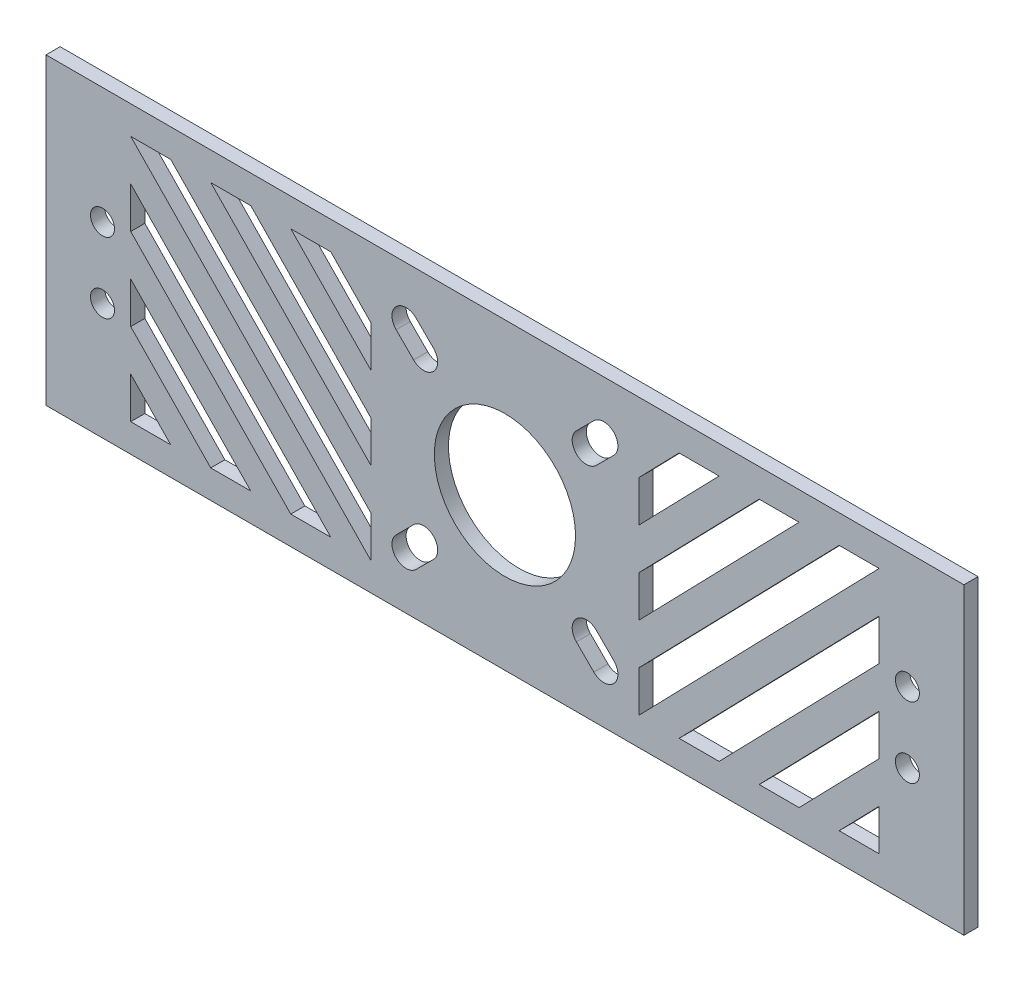
SolidWorks part; units mm, degrees
material "黑板"
ref_plane "前视基准面" through (0, 0, 0) normal (0, 0, 1) x (1, 0, 0)
ref_plane "上视基准面" through (0, 0, 0) normal (0, 1, 0) x (1, 0, 0)
ref_plane "右视基准面" through (0, 0, 0) normal (1, 0, 0) x (0, 0, -1)
sketch "草图1" plane through (0, 0, 0) normal (0, 0, 1) x (1, 0, 0)
  line L1 (-65, 21.5) -> (65, 21.5)
  line L2 (-65, 21.5) -> (-65, -21.5)
  line L3 (-65, -21.5) -> (65, -21.5)
  line L4 (65, 21.5) -> (65, -21.5)
  line L5 (-65, 21.5) -> (65, -21.5) construction
  line L6 (-65, -21.5) -> (65, 21.5) construction
  point P0 (0, 0)
  dimension "D1" = 130
  dimension "D2" = 43
extrude "凸台-拉伸1" add sketch "草图1" along normal blind 2
sketch "草图2" plane through (0, 0, 2) normal (0, 0, 1) x (1, 0, 0)
  line L0 (-14, 14) -> (-11.5251, 11.5251) construction
  line L1 (-16, 16) -> (16, 16) construction
  line L2 (-16, 16) -> (-16, -16) construction
  line L3 (-16, -16) -> (16, -16) construction
  line L4 (16, 16) -> (16, -16) construction
  line L5 (-16, 16) -> (16, -16) construction
  line L6 (-16, -16) -> (16, 16) construction
  line L7 (-12.5858, 15.4142) -> (-10.1109, 12.9393)
  line L8 (-15.4142, 12.5858) -> (-12.9393, 10.1109)
  line L9 (14, 14) -> (11.5251, 11.5251) construction
  line L10 (15.4142, 12.5858) -> (12.9393, 10.1109)
  line L11 (12.5858, 15.4142) -> (10.1109, 12.9393)
  line L12 (14, -14) -> (11.5251, -11.5251) construction
  line L13 (12.5858, -15.4142) -> (10.1109, -12.9393)
  line L14 (15.4142, -12.5858) -> (12.9393, -10.1109)
  line L15 (-14, -14) -> (-11.5251, -11.5251) construction
  line L16 (-15.4142, -12.5858) -> (-12.9393, -10.1109)
  line L17 (-12.5858, -15.4142) -> (-10.1109, -12.9393)
  arc A0 (-12.5858, 15.4142) -> (-15.4142, 12.5858) centre (-14, 14) ccw
  arc A1 (-12.9393, 10.1109) -> (-10.1109, 12.9393) centre (-11.5251, 11.5251) ccw
  arc A2 (15.4142, 12.5858) -> (12.5858, 15.4142) centre (14, 14) ccw
  arc A3 (10.1109, 12.9393) -> (12.9393, 10.1109) centre (11.5251, 11.5251) ccw
  arc A4 (12.5858, -15.4142) -> (15.4142, -12.5858) centre (14, -14) ccw
  arc A5 (12.9393, -10.1109) -> (10.1109, -12.9393) centre (11.5251, -11.5251) ccw
  arc A6 (-15.4142, -12.5858) -> (-12.5858, -15.4142) centre (-14, -14) ccw
  arc A7 (-10.1109, -12.9393) -> (-12.9393, -10.1109) centre (-11.5251, -11.5251) ccw
  point P0 (0, 0)
  point P8 (-12.7626, 12.7626)
  point P13 (0, 0)
  point P14 (11.5251, 11.5251)
  point P18 (12.7626, 12.7626)
  point P25 (12.7626, -12.7626)
  point P32 (-12.7626, -12.7626)
  point P37 (0, 0)
  dimension "D3" = 2
  dimension "D1" = 32
  dimension "D2" = 3.5
  dimension "D4" = 4
extrude "切除-拉伸1" cut sketch "草图2" against normal through all
sketch "草图3" plane through (0, 0, 2) normal (0, 0, 1) x (1, 0, 0)
  line L0 (57, -5) -> (57, 5) construction
  line L1 (57, 0) -> (65, 0) construction
  line L2 (65, -21.5) -> (65, 21.5) construction
  line L3 (0, 0) -> (0, 32.0098) construction
  circle A0 centre (57, 5) radius 1.7
  circle A1 centre (57, -5) radius 1.7
  circle A2 centre (-57, -5) radius 1.7
  circle A3 centre (-57, 5) radius 1.7
  dimension "D1" = 10
  dimension "D2" = 8
  dimension "3.4" = 3.4
extrude "切除-拉伸2" cut sketch "草图3" against normal through all
sketch "草图4" plane through (0, 0, 2) normal (0, 0, 1) x (1, 0, 0)
  line L0 (-53, 17.5) -> (-53, -17.5)
  line L1 (-53, -17.5) -> (-19, -17.5)
  line L2 (-19, -17.5) -> (-19, 17.5)
  line L3 (-19, 17.5) -> (-53, 17.5)
  line L4 (-57, 5) -> (-57, -5) construction
  line L5 (65, 21.5) -> (-65, 21.5) construction
  line L6 (-65, -21.5) -> (65, -21.5) construction
  line L7 (0, 0) -> (0, 37.7139) construction
  line L8 (19, -17.5) -> (19, 17.5)
  line L9 (53, -17.5) -> (19, -17.5)
  line L10 (53, 17.5) -> (53, -17.5)
  line L11 (19, 17.5) -> (53, 17.5)
  arc A0 (-12.5858, 15.4142) -> (-15.4142, 12.5858) centre (-14, 14) ccw construction
  circle A1 centre (0, 0) radius 10
  dimension "D5" = 20
  dimension "D1" = 4
  dimension "D2" = 4
  dimension "D3" = 4
  dimension "D4" = 5
extrude "切除-拉伸3" cut sketch "草图4" against normal through all
sketch "草图6" plane through (0, 0, 2) normal (0, 0, 1) x (1, 0, 0)
  line L0 (-53, 17.5) -> (-19, -17.5)
  line L1 (-47.3333, 17.5) -> (-13.3333, -17.5)
  line L2 (-41.6667, 17.5) -> (-7.6667, -17.5)
  line L3 (-36, 17.5) -> (-2, -17.5)
  line L4 (-30.3333, 17.5) -> (3.6667, -17.5)
  line L5 (-58.6667, 17.5) -> (-24.6667, -17.5)
  line L6 (-53, 17.5) -> (-19, -17.5)
  line L7 (-47.3333, 17.5) -> (-13.3333, -17.5)
  line L8 (-41.6667, 17.5) -> (-7.6667, -17.5)
  line L9 (-36, 17.5) -> (-2, -17.5)
  line L10 (-64.3333, 17.5) -> (-30.3333, -17.5)
  line L11 (-58.6667, 17.5) -> (-24.6667, -17.5)
  line L12 (-53, 17.5) -> (-19, -17.5)
  line L13 (-47.3333, 17.5) -> (-13.3333, -17.5)
  line L14 (-41.6667, 17.5) -> (-7.6667, -17.5)
  line L15 (-70, 17.5) -> (-36, -17.5)
  line L16 (-64.3333, 17.5) -> (-30.3333, -17.5)
  line L17 (-58.6667, 17.5) -> (-24.6667, -17.5)
  line L18 (-53, 17.5) -> (-19, -17.5)
  line L19 (-47.3333, 17.5) -> (-13.3333, -17.5)
  line L20 (-75.6667, 17.5) -> (-41.6667, -17.5)
  line L21 (-70, 17.5) -> (-36, -17.5)
  line L22 (-64.3333, 17.5) -> (-30.3333, -17.5)
  line L23 (-58.6667, 17.5) -> (-24.6667, -17.5)
  line L24 (-53, 17.5) -> (-19, -17.5)
  line L25 (-81.3333, 17.5) -> (-47.3333, -17.5)
  line L26 (-75.6667, 17.5) -> (-41.6667, -17.5)
  line L27 (-70, 17.5) -> (-36, -17.5)
  line L28 (-64.3333, 17.5) -> (-30.3333, -17.5)
  line L29 (-58.6667, 17.5) -> (-24.6667, -17.5)
  line L30 (-87, 17.5) -> (-53, -17.5)
  line L31 (-81.3333, 17.5) -> (-47.3333, -17.5)
  line L32 (-75.6667, 17.5) -> (-41.6667, -17.5)
  line L33 (-70, 17.5) -> (-36, -17.5)
  line L34 (-64.3333, 17.5) -> (-30.3333, -17.5)
  line L40 (-24.6667, 17.5) -> (9.3333, -17.5)
  line L41 (-19, 17.5) -> (15, -17.5)
  line L43 (-30.3333, 17.5) -> (3.6667, -17.5)
  line L44 (-24.6667, 17.5) -> (9.3333, -17.5)
  line L46 (-36, 17.5) -> (-2, -17.5)
  line L47 (-30.3333, 17.5) -> (3.6667, -17.5)
  line L49 (-41.6667, 17.5) -> (-7.6667, -17.5)
  line L50 (-36, 17.5) -> (-2, -17.5)
  line L52 (-47.3333, 17.5) -> (-13.3333, -17.5)
  line L53 (-41.6667, 17.5) -> (-7.6667, -17.5)
  line L55 (-53, 17.5) -> (-19, -17.5)
  line L56 (-47.3333, 17.5) -> (-13.3333, -17.5)
  line L58 (-58.6667, 17.5) -> (-24.6667, -17.5)
  line L59 (-53, 17.5) -> (-19, -17.5)
  line L64 (-19, 17.5) -> (-53, 17.5) construction
  line L66 (-53, 17.5) -> (-19, 17.5)
  line L67 (-53, 17.5) -> (-53, -17.5)
  line L68 (-53, -17.5) -> (-19, -17.5)
  line L69 (-19, 17.5) -> (-19, -17.5)
  point P4 (-19.4424, 17.5)
  line M2 (-53, 17.5) -> (-19, 17.5)
  line M3 (-19, 17.5) -> (-19, -17.5)
  line M4 (-19, -17.5) -> (-53, -17.5)
  line M5 (-53, -17.5) -> (-53, 17.5)
  dimension "D1" = 7
  dimension "D2" = 7
extrude "凸台-拉伸2" add sketch "草图6" against normal through all contours L25 L20 M5 M4 | L15 L10 M5 M4 | L5 L0 M5 M4 | L2 L1 M2 M3 | L4 L3 M2 M3 | L40 M2 M3 | L67 L66 L69 L68
mirror "镜向1" about plane through (0, 0, 0) normal (1, 0, 0) of "凸台-拉伸2"
